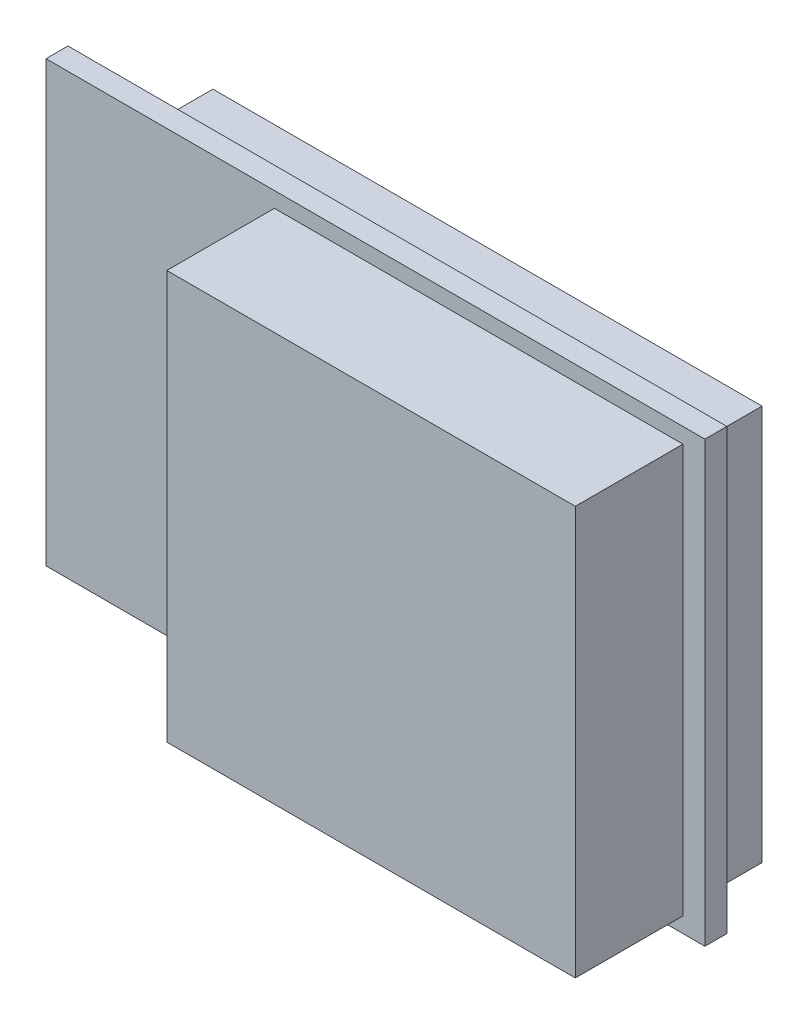
SolidWorks part; units mm, degrees
ref_plane "Front Plane" through (0, 0, 0) normal (0, 0, 1) x (1, 0, 0)
ref_plane "Top Plane" through (0, 0, 0) normal (0, 1, 0) x (1, 0, 0)
ref_plane "Right Plane" through (0, 0, 0) normal (1, 0, 0) x (0, 0, -1)
sketch "Sketch1" plane through (0, 0, 0) normal (0, 0, 1) x (1, 0, 0)
  line L1 (-15, -10) -> (15, -10)
  line L2 (-15, -10) -> (-15, 10)
  line L3 (-15, 10) -> (15, 10)
  line L4 (15, -10) -> (15, 10)
  line L5 (-15, -10) -> (15, 10) construction
  line L6 (-15, 10) -> (15, -10) construction
  point P0 (0, 0)
  dimension "D1" = 20
  dimension "D2" = 30
extrude "Boss-Extrude1" add sketch "Sketch1" along normal blind 1
sketch "Sketch2" plane through (0, 0, 0) normal (0, 0, -1) x (-1, 0, 0)
  line L1 (15, -10) -> (12, -10)
  line L2 (15, -10) -> (15, 2.8)
  line L3 (15, 2.8) -> (12, 2.8)
  line L4 (12, -10) -> (12, 2.8)
  dimension "D1" = 12.8
  dimension "D2" = 3
extrude "Boss-Extrude2" add sketch "Sketch2" along normal blind 2.2
sketch "Sketch3" plane through (0, 0, -2.2) normal (0, 0, -1) x (-1, 0, 0)
  line L0 (12, -10) -> (15, -10) construction
  line L1 (13, -9.1) -> (14, -9.1)
  line L2 (13, -9.1) -> (13, -8.1)
  line L3 (13, -8.1) -> (14, -8.1)
  line L4 (14, -9.1) -> (14, -8.1)
  line L5 (13, -9.1) -> (14, -8.1) construction
  line L6 (13, -8.1) -> (14, -9.1) construction
  line L7 (15, -10) -> (15, 2.8) construction
  point P0 (13.5, -8.6)
  point P9 (15, -7.4553)
  dimension "D1" = 1
  dimension "D2" = 1
  dimension "D3" = 1.4
  dimension "D4" = 1.5
extrude "Boss-Extrude3" add sketch "Sketch3" along normal blind 5
pattern_linear "LPattern1" count 6 spacing 2 along (0, 1, 0) of "Boss-Extrude3"
sketch "Sketch4" plane through (0, 0, 0) normal (0, 0, -1) x (-1, 0, 0)
  line L0 (12, -10) -> (-15, -10) construction
  line L1 (11, 9) -> (-14, 9)
  line L2 (11, 9) -> (11, -9)
  line L3 (11, -9) -> (-14, -9)
  line L4 (-14, 9) -> (-14, -9)
  line L5 (11, 9) -> (-14, -9) construction
  line L6 (11, -9) -> (-14, 9) construction
  line L7 (-15, -10) -> (-15, 10) construction
  line L8 (-15, 10) -> (15, 10) construction
  line L9 (12, 2.8) -> (12, -10) construction
  point P0 (-1.5, 0)
  dimension "D1" = 1
  dimension "D2" = 1
  dimension "D3" = 1
  dimension "D4" = 1
extrude "Boss-Extrude4" add sketch "Sketch4" along normal blind 2.6
sketch "Sketch5" plane through (0, 0, 1) normal (0, 0, 1) x (1, 0, 0)
  line L1 (-4.6, -9.3) -> (14, -9.3)
  line L2 (-4.6, -9.3) -> (-4.6, 9.3)
  line L3 (-4.6, 9.3) -> (14, 9.3)
  line L4 (14, -9.3) -> (14, 9.3)
  line L5 (-4.6, -9.3) -> (14, 9.3) construction
  line L6 (-4.6, 9.3) -> (14, -9.3) construction
  line L8 (15, -10) -> (15, 10) construction
  point P0 (4.7, 0)
  dimension "D1" = 18.6
  dimension "D2" = 18.6
  dimension "D3" = 1
extrude "Boss-Extrude5" add sketch "Sketch5" along normal blind 4.9
